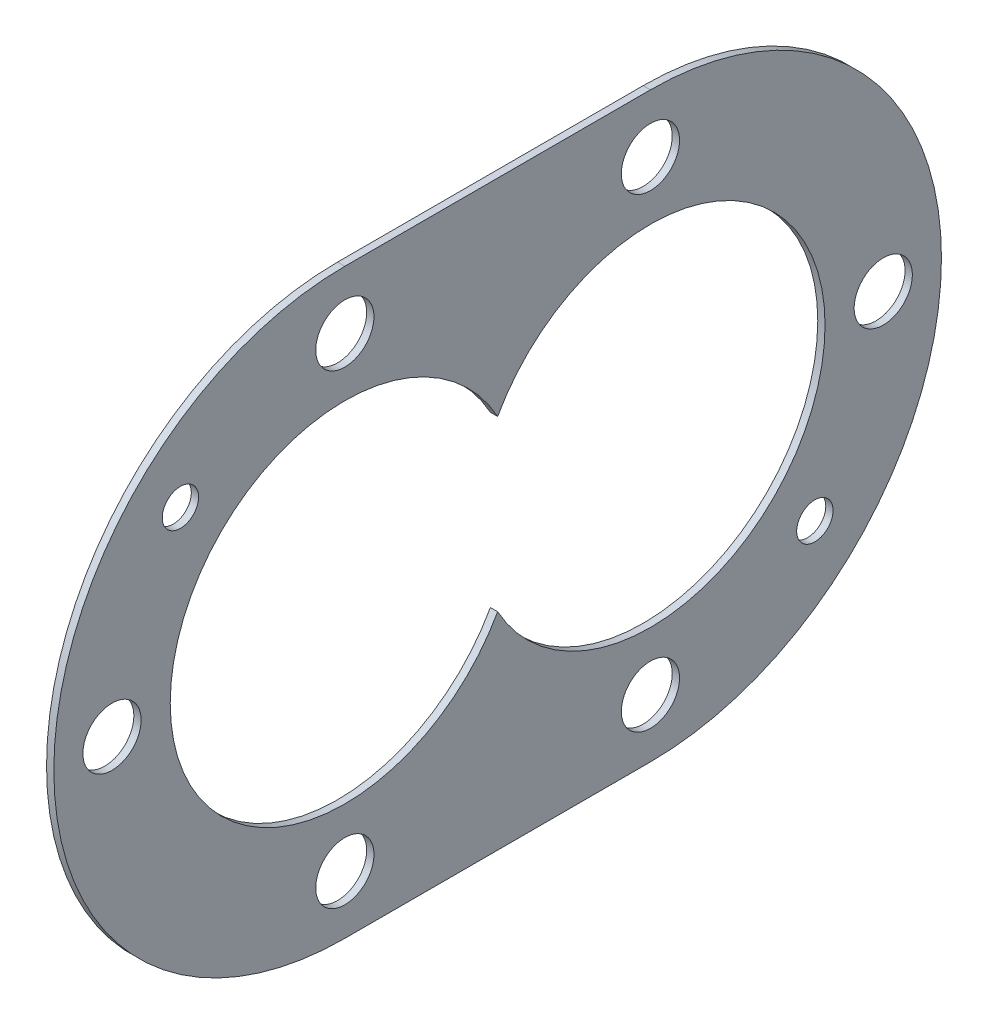
SolidWorks part; units mm, degrees
ref_plane "前视基准面" through (0, 0, 0) normal (0, 0, 1) x (1, 0, 0)
ref_plane "上视基准面" through (0, 0, 0) normal (0, 1, 0) x (1, 0, 0)
ref_plane "右视基准面" through (0, 0, 0) normal (1, 0, 0) x (0, 0, -1)
other "Configuration Table"
ref_plane "P_GASKET" through (-31, 0, 0) normal (1, 0, 0) x (0, 0, -1)
sketch "草图1" plane through (-31, 0, 0) normal (1, 0, 0) x (0, 0, -1)
  line L0 (-104, -40) -> (-62, -40)
  line L1 (-62, 40) -> (-104, 40)
  arc A0 (-62, -40) -> (-62, 40) centre (-62, 0) ccw
  arc A1 (-104, 40) -> (-104, -40) centre (-104, 0) ccw
extrude "01_GASKET" add sketch "草图1" along normal blind 1
ref_plane "P_02_HOLE_UP" through (-32, 0, 0) normal (1, 0, 0) x (0, 0, -1)
sketch "草图2" plane through (-32, 0, 0) normal (1, 0, 0) x (0, 0, -1)
  circle A0 centre (-104, 0) radius 24
extrude "02_HOLE_UP" cut sketch "草图2" along normal blind 3
ref_plane "P_03_HOLE_LO" through (-32, 0, 0) normal (1, 0, 0) x (0, 0, -1)
sketch "草图3" plane through (-32, 0, 0) normal (1, 0, 0) x (0, 0, -1)
  circle A0 centre (-62, 0) radius 24
extrude "03_HOLE_LO" cut sketch "草图3" along normal blind 3
ref_plane "P_04_BOLT_0" through (-32, 0, 0) normal (1, 0, 0) x (0, 0, -1)
sketch "草图4" plane through (-32, 0, 0) normal (1, 0, 0) x (0, 0, -1)
  circle A0 centre (-104, 32) radius 4
extrude "04_BOLT_0" cut sketch "草图4" along normal blind 3
ref_plane "P_04_BOLT_1" through (-32, 0, 0) normal (1, 0, 0) x (0, 0, -1)
sketch "草图5" plane through (-32, 0, 0) normal (1, 0, 0) x (0, 0, -1)
  circle A0 centre (-104, -32) radius 4
extrude "04_BOLT_1" cut sketch "草图5" along normal blind 3
ref_plane "P_04_BOLT_2" through (-32, 0, 0) normal (1, 0, 0) x (0, 0, -1)
sketch "草图6" plane through (-32, 0, 0) normal (1, 0, 0) x (0, 0, -1)
  circle A0 centre (-62, 32) radius 4
extrude "04_BOLT_2" cut sketch "草图6" along normal blind 3
ref_plane "P_04_BOLT_3" through (-32, 0, 0) normal (1, 0, 0) x (0, 0, -1)
sketch "草图7" plane through (-32, 0, 0) normal (1, 0, 0) x (0, 0, -1)
  circle A0 centre (-62, -32) radius 4
extrude "04_BOLT_3" cut sketch "草图7" along normal blind 3
ref_plane "P_04_BOLT_4" through (-32, 0, 0) normal (1, 0, 0) x (0, 0, -1)
sketch "草图8" plane through (-32, 0, 0) normal (1, 0, 0) x (0, 0, -1)
  circle A0 centre (-136, 0) radius 4
extrude "04_BOLT_4" cut sketch "草图8" along normal blind 3
ref_plane "P_04_BOLT_5" through (-32, 0, 0) normal (1, 0, 0) x (0, 0, -1)
sketch "草图9" plane through (-32, 0, 0) normal (1, 0, 0) x (0, 0, -1)
  circle A0 centre (-30, 0) radius 4
extrude "04_BOLT_5" cut sketch "草图9" along normal blind 3
ref_plane "P_05_DOWEL_0" through (-32, 0, 0) normal (1, 0, 0) x (0, 0, -1)
sketch "草图10" plane through (-32, 0, 0) normal (1, 0, 0) x (0, 0, -1)
  circle A0 centre (-126.6, 22.6) radius 2.5
extrude "05_DOWEL_0" cut sketch "草图10" along normal blind 3
ref_plane "P_05_DOWEL_1" through (-32, 0, 0) normal (1, 0, 0) x (0, 0, -1)
sketch "草图11" plane through (-32, 0, 0) normal (1, 0, 0) x (0, 0, -1)
  circle A0 centre (-39.4, -22.6) radius 2.5
extrude "05_DOWEL_1" cut sketch "草图11" along normal blind 3
